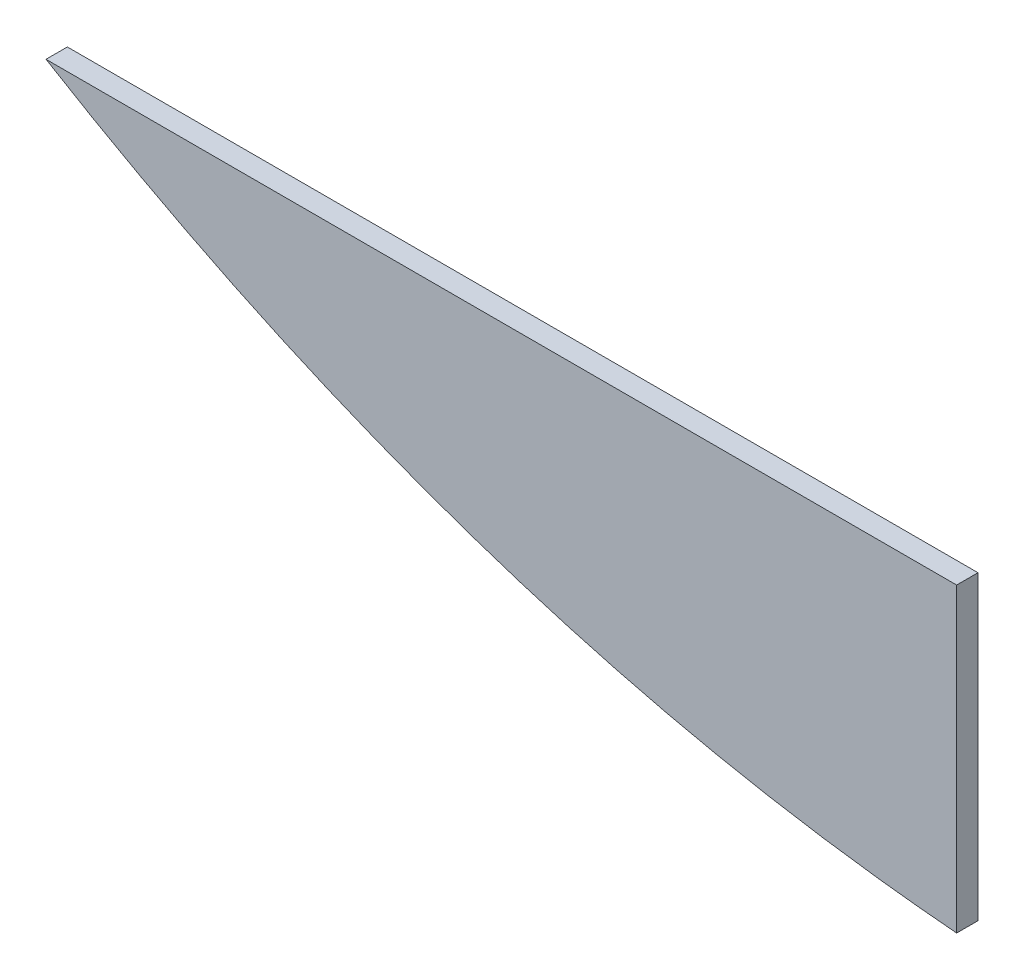
SolidWorks part; units mm, degrees
ref_plane "Front Plane" through (0, 0, 0) normal (0, 0, 1) x (1, 0, 0)
ref_plane "Top Plane" through (0, 0, 0) normal (0, 1, 0) x (1, 0, 0)
ref_plane "Right Plane" through (0, 0, 0) normal (1, 0, 0) x (0, 0, -1)
sketch "Sketch1" plane through (0, 0, 0) normal (0, 0, 1) x (1, 0, 0)
  line L0 (67.7051, 22.4076) -> (-67.7051, 22.4076)
  line L1 (67.7051, 22.4076) -> (67.7051, -22.4076)
  spline S0 degree 2 poles (67.7051, -22.4076) (-3.3636, -16.4643) (-67.7051, 22.4076) knots 0 0 0 1 1 1
extrude "Boss-Extrude1" add sketch "Sketch1" along normal blind 3.175
